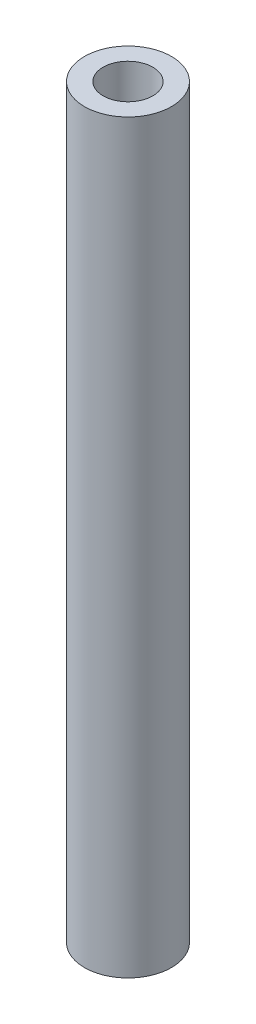
SolidWorks part; units mm, degrees
ref_plane "前视基准面" through (0, 0, 0) normal (0, 0, 1) x (1, 0, 0)
ref_plane "上视基准面" through (0, 0, 0) normal (0, 1, 0) x (1, 0, 0)
ref_plane "右视基准面" through (0, 0, 0) normal (1, 0, 0) x (0, 0, -1)
other "Configuration Table"
sketch "草图1" plane through (0, 0, 0) normal (0, 1, 0) x (1, 0, 0)
  circle A0 centre (0, 0) radius 1.75
  circle A1 centre (0, 0) radius 1
  dimension "D1" = 3.5
  dimension "D2" = 2
extrude "凸台-拉伸1" add sketch "草图1" along normal blind 30
